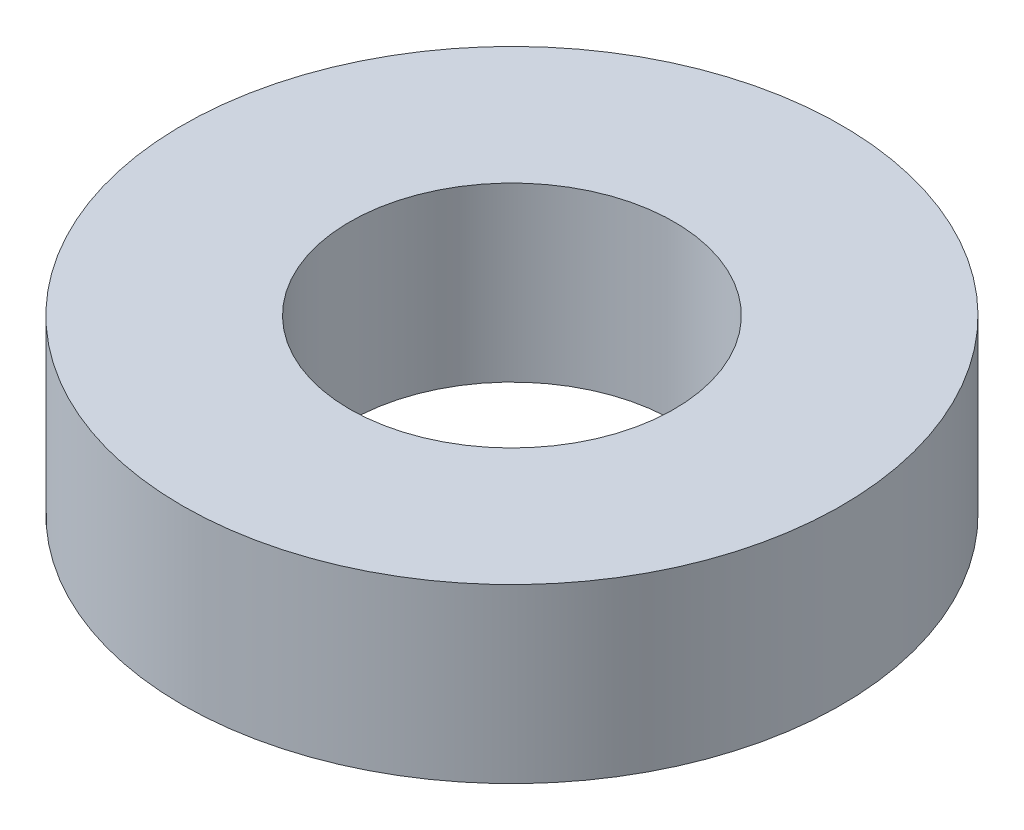
SolidWorks part; units mm, degrees
ref_plane "前视基准面" through (0, 0, 0) normal (0, 0, 1) x (1, 0, 0)
ref_plane "上视基准面" through (0, 0, 0) normal (0, 1, 0) x (1, 0, 0)
ref_plane "右视基准面" through (0, 0, 0) normal (1, 0, 0) x (0, 0, -1)
other "Configuration Table"
sketch "草图1" plane through (0, 0, 0) normal (0, 1, 0) x (1, 0, 0)
  circle A0 centre (0, 0) radius 3.25
  circle A1 centre (0, 0) radius 1.6
  dimension "D1" = 3.2
  dimension "D2" = 6.5
extrude "凸台-拉伸1" add sketch "草图1" along normal blind 1.7
